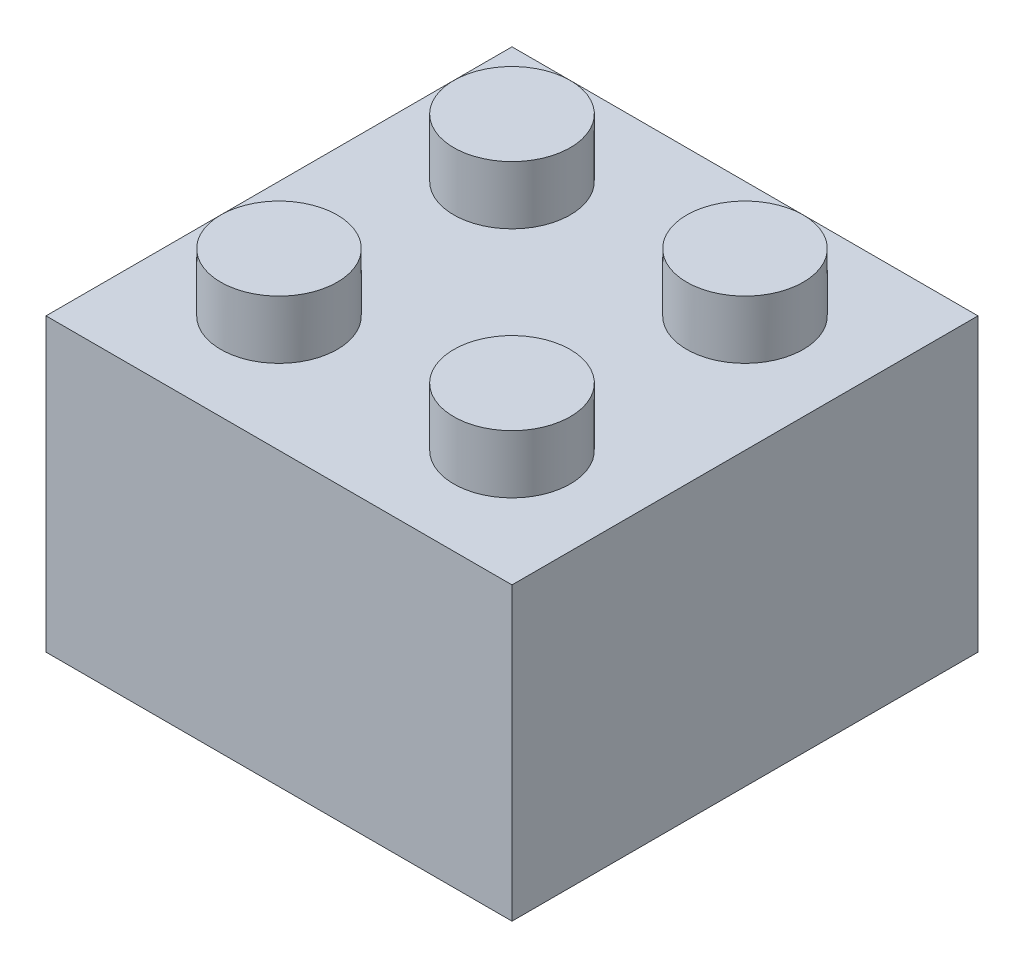
SolidWorks part; units mm, degrees
ref_plane "Front Plane" through (0, 0, 0) normal (0, 0, 1) x (1, 0, 0)
ref_plane "Top Plane" through (0, 0, 0) normal (0, 1, 0) x (1, 0, 0)
ref_plane "Right Plane" through (0, 0, 0) normal (1, 0, 0) x (0, 0, -1)
sketch "Sketch1" plane through (0, 0, 0) normal (0, 1, 0) x (1, 0, 0)
  line L1 (-8, 8) -> (8, 8)
  line L2 (-8, 8) -> (-8, -8)
  line L3 (-8, -8) -> (8, -8)
  line L4 (8, 8) -> (8, -8)
  line L5 (-8, 8) -> (8, -8) construction
  line L6 (-8, -8) -> (8, 8) construction
  point P0 (0, 0)
  dimension "D1" = 16
  dimension "D2" = 16
extrude "Boss-Extrude1" add sketch "Sketch1" along normal blind 10 contours L2 L3 L4 L1
sketch "Sketch2" plane through (0, 10, 0) normal (0, 1, 0) x (1, 0, 0)
  line L0 (-8, 0) -> (0, 0) construction
  line L1 (-8, 8) -> (-8, -8) construction
  line L3 (0, 8) -> (0, 0) construction
  line L4 (-8, 8) -> (8, 8) construction
  line L5 (8, 8) -> (8, -8) construction
  circle A0 centre (4, 4) radius 2
  circle A1 centre (-4, 4) radius 2
  circle A2 centre (4, -4) radius 2
  circle A3 centre (-4, -4) radius 2
  dimension "D3" = 4
  dimension "D1" = 4
  dimension "D2" = 4
extrude "Boss-Extrude2" add sketch "Sketch2" along normal blind 2
shell "Shell1" thickness 1
sketch "Sketch3" plane through (0, 9, 0) normal (0, -1, 0) x (1, 0, 0)
  circle A0 centre (0, 0) radius 1.7
  circle A1 centre (0, 0) radius 2.7
  dimension "D1" = 5.4
  dimension "D2" = 3.4
extrude "Boss-Extrude3" add sketch "Sketch3" along normal blind 9
